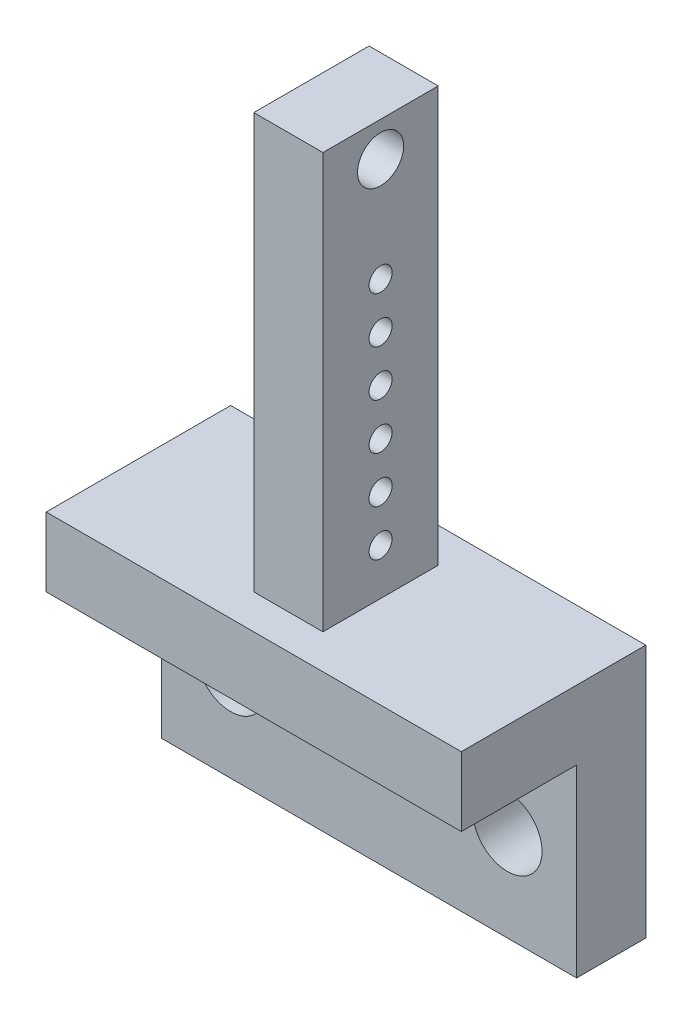
SolidWorks part; units mm, degrees
ref_plane "Plan de face" through (0, 0, 0) normal (0, 0, 1) x (1, 0, 0)
ref_plane "Plan de dessus" through (0, 0, 0) normal (0, 1, 0) x (1, 0, 0)
ref_plane "Plan de droite" through (0, 0, 0) normal (1, 0, 0) x (0, 0, -1)
sketch "Esquisse1" plane through (0, 0, 0) normal (0, 0, 1) x (1, 0, 0)
  line L0 (-8.2327, 4.6763) -> (-8.2327, -6.3237) construction
  line L1 (-17.2327, 4.6763) -> (0.7673, 4.6763)
  line L2 (-17.2327, 4.6763) -> (-17.2327, -6.3237)
  line L3 (-17.2327, -6.3237) -> (0.7673, -6.3237)
  line L4 (0.7673, 4.6763) -> (0.7673, -6.3237)
  line L5 (-17.2327, 4.6763) -> (0.7673, -6.3237) construction
  line L6 (-17.2327, -6.3237) -> (0.7673, 4.6763) construction
  circle A0 centre (-14.2327, -2.3237) radius 1.5
  circle A1 centre (-2.2327, -2.3237) radius 1.5
  point P0 (-8.2327, -0.8237)
  dimension "D3" = 4
  dimension "D1" = 18
  dimension "D2" = 11
  dimension "D4" = 4
  dimension "D5" = 6
  dimension "D6" = 6
extrude "Boss.-Extru.1" add sketch "Esquisse1" along normal blind 3
sketch "Esquisse2" plane through (0, 0, 3) normal (0, 0, 1) x (1, 0, 0)
  line L0 (-17.2327, 4.6763) -> (-17.2327, -6.3237) construction
  line L1 (0.7673, 4.6763) -> (-17.2327, 4.6763)
  line L2 (0.7673, 4.6763) -> (0.7673, 1.6763)
  line L3 (0.7673, 1.6763) -> (-17.2327, 1.6763)
  line L4 (-17.2327, 4.6763) -> (-17.2327, 1.6763)
  dimension "D1" = 3
extrude "Boss.-Extru.2" add sketch "Esquisse2" along normal blind 5
sketch "Esquisse3" plane through (0, 4.6763, 0) normal (0, 1, 0) x (1, 0, 0)
  line L0 (-8.2327, -8) -> (-8.2327, 0) construction
  line L1 (0.7673, -8) -> (-17.2327, -8) construction
  line L2 (0.7673, 0) -> (-17.2327, 0) construction
  line L4 (-9.7327, -1.5) -> (-6.7327, -1.5)
  line L5 (-9.7327, -1.5) -> (-9.7327, -6.5)
  line L6 (-9.7327, -6.5) -> (-6.7327, -6.5)
  line L7 (-6.7327, -1.5) -> (-6.7327, -6.5)
  line L8 (-9.7327, -1.5) -> (-6.7327, -6.5) construction
  line L9 (-9.7327, -6.5) -> (-6.7327, -1.5) construction
  point P6 (-8.2327, -4)
  dimension "D1" = 3
  dimension "D2" = 5
extrude "Boss.-Extru.3" add sketch "Esquisse3" along normal blind 18
sketch "Esquisse4" plane through (-6.7327, 0, 0) normal (1, 0, 0) x (0, 0, -1)
  line L0 (-4, 4.6763) -> (-4, 22.6763) construction
  line L1 (-6.5, 4.6763) -> (-1.5, 4.6763) construction
  line L2 (-6.5, 22.6763) -> (-1.5, 22.6763) construction
  circle A0 centre (-4, 21.1763) radius 1
  circle A1 centre (-4, 16.6763) radius 0.5
  circle A2 centre (-4, 14.6763) radius 0.5
  circle A3 centre (-4, 12.6763) radius 0.5
  circle A4 centre (-4, 10.6763) radius 0.5
  circle A5 centre (-4, 8.6763) radius 0.5
  circle A6 centre (-4, 6.6763) radius 0.5
  dimension "D1" = 1.5
  dimension "D2" = 4.5
  dimension "D3" = 2
  dimension "D7" = 2
  dimension "D4" = 2
  dimension "D5" = 2
  dimension "D6" = 2
extrude "Enlèv. mat.-Extru.1" cut sketch "Esquisse4" against normal blind 18 contours L0 A6 | A6 L0 | A5 | A4 | A3 | A2 | A1 | A0
